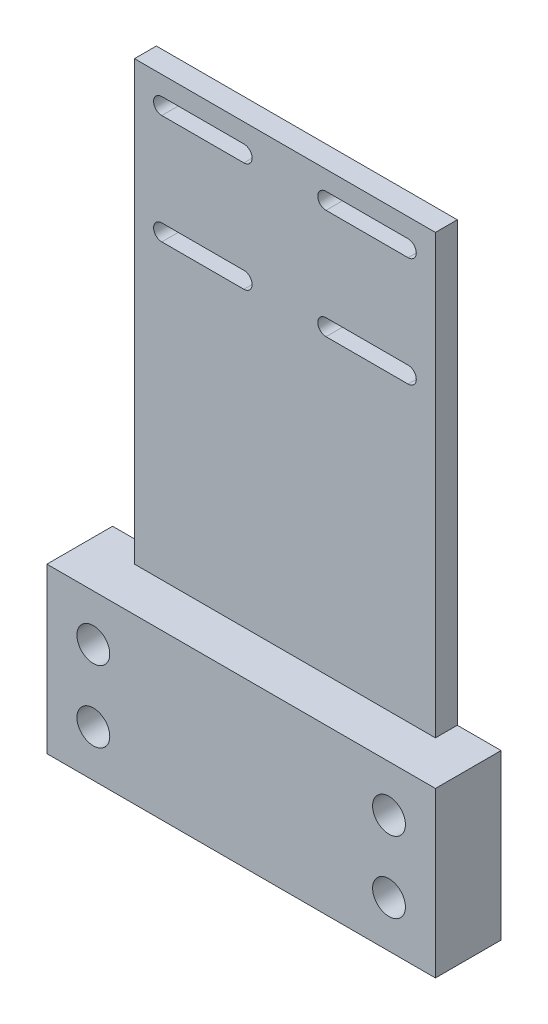
SolidWorks part; units mm, degrees
ref_plane "Front Plane" through (0, 0, 0) normal (0, 0, 1) x (1, 0, 0)
ref_plane "Top Plane" through (0, 0, 0) normal (0, 1, 0) x (1, 0, 0)
ref_plane "Right Plane" through (0, 0, 0) normal (1, 0, 0) x (0, 0, -1)
sketch "Sketch1" plane through (0, 0, 0) normal (0, 0, 1) x (1, 0, 0)
  line L0 (20, 0) -> (-20, 40) construction
  line L2 (-27.5, 35) -> (27.5, 35)
  line L3 (-27.5, 35) -> (-27.5, 5)
  line L4 (-27.5, 5) -> (27.5, 5)
  line L5 (27.5, 35) -> (27.5, 5)
  line L6 (-27.5, 35) -> (27.5, 5) construction
  line L7 (-27.5, 5) -> (27.5, 35) construction
  line L8 (22.5, 31.5) -> (7.5, 31.5)
  line L10 (22.5, 28.5) -> (7.5, 28.5)
  line L12 (22.5, 31.5) -> (7.5, 28.5) construction
  line L13 (22.5, 28.5) -> (7.5, 31.5) construction
  line L14 (22.5, 8.5) -> (7.5, 8.5)
  line L16 (22.5, 11.5) -> (7.5, 11.5)
  line L18 (22.5, 8.5) -> (7.5, 11.5) construction
  line L19 (22.5, 11.5) -> (7.5, 8.5) construction
  line L20 (-22.5, 8.5) -> (-7.5, 8.5)
  line L22 (-22.5, 11.5) -> (-7.5, 11.5)
  line L24 (-22.5, 8.5) -> (-7.5, 11.5) construction
  line L25 (-22.5, 11.5) -> (-7.5, 8.5) construction
  line L26 (-7.5, 28.5) -> (-22.5, 28.5)
  line L28 (-7.5, 31.5) -> (-22.5, 31.5)
  line L30 (-7.5, 28.5) -> (-22.5, 31.5) construction
  line L31 (-7.5, 31.5) -> (-22.5, 28.5) construction
  arc A0 (22.5, 28.5) -> (22.5, 31.5) centre (22.5, 30) ccw
  arc A1 (7.5, 28.5) -> (7.5, 31.5) centre (7.5, 30) cw
  arc A2 (22.5, 8.5) -> (22.5, 11.5) centre (22.5, 10) ccw
  arc A3 (7.5, 8.5) -> (7.5, 11.5) centre (7.5, 10) cw
  arc A4 (-7.5, 8.5) -> (-7.5, 11.5) centre (-7.5, 10) ccw
  arc A5 (-22.5, 8.5) -> (-22.5, 11.5) centre (-22.5, 10) cw
  arc A6 (-7.5, 28.5) -> (-7.5, 31.5) centre (-7.5, 30) ccw
  arc A7 (-22.5, 28.5) -> (-22.5, 31.5) centre (-22.5, 30) cw
  point P4 (0, 20)
  point P9 (15, 30)
  point P15 (15, 10)
  point P21 (-15, 10)
  point P27 (-15, 30)
  dimension "D1" = 55
  dimension "D2" = 30
  dimension "D3" = 3
  dimension "D4" = 15
  dimension "D5" = 3
  dimension "D6" = 15
extrude "Boss-Extrude1" add sketch "Sketch1" along normal blind 4
sketch "Sketch4" plane through (0, 5, 0) normal (0, -1, 0) x (1, 0, 0)
  line L1 (27.5, 4) -> (-27.5, 4)
  line L2 (27.5, 4) -> (27.5, 0)
  line L3 (27.5, 0) -> (-27.5, 0)
  line L4 (-27.5, 4) -> (-27.5, 0)
extrude "Boss-Extrude2" add sketch "Sketch4" along normal blind 80
sketch "Sketch5" plane through (-27.5, 0, 0) normal (-1, 0, 0) x (0, 0, 1)
  line L0 (0, 35) -> (0, -75) construction
  line L1 (4, -75) -> (0, -75)
  line L2 (4, -75) -> (4, -45)
  line L3 (4, -45) -> (0, -45)
  line L4 (0, -75) -> (0, -45)
  dimension "D1" = 30
extrude "Boss-Extrude3" add sketch "Sketch5" along normal blind 8
sketch "Sketch6" plane through (27.5, 0, 0) normal (1, 0, 0) x (0, 0, -1)
  line L0 (-4, -75) -> (-4, 35) construction
  line L1 (0, -75) -> (-4, -75)
  line L2 (0, -75) -> (0, -45)
  line L3 (0, -45) -> (-4, -45)
  line L4 (-4, -75) -> (-4, -45)
  dimension "D1" = 30
extrude "Boss-Extrude4" add sketch "Sketch6" along normal blind 8
sketch "Sketch7" plane through (0, 0, 4) normal (0, 0, 1) x (1, 0, 0)
  line L1 (-35.5, -75) -> (35.5, -75)
  line L2 (-35.5, -75) -> (-35.5, -45)
  line L3 (-35.5, -45) -> (35.5, -45)
  line L4 (35.5, -75) -> (35.5, -45)
extrude "Boss-Extrude5" add sketch "Sketch7" along normal blind 8
sketch "Sketch8" plane through (0, 0, 0) normal (0, 0, -1) x (-1, 0, 0)
  line L0 (-35.5, -45) -> (-27.0147, -53.4853)
  line L1 (-35.5, -75) -> (-27.0147, -66.5147)
  line L2 (35.5, -45) -> (27.0147, -53.4853)
  line L3 (35.5, -75) -> (27.0147, -66.5147)
  circle A0 centre (-27.0147, -53.4853) radius 5
  circle A1 centre (-27.0147, -66.5147) radius 5
  circle A2 centre (27.0147, -53.4853) radius 5
  circle A3 centre (27.0147, -66.5147) radius 5
sketch "Sketch9" plane through (0, 0, 12) normal (0, 0, 1) x (1, 0, 0)
  circle A0 centre (27.0147, -66.5147) radius 3
  circle A1 centre (27.0147, -53.4853) radius 3
  circle A2 centre (-27.0147, -53.4853) radius 3
  circle A3 centre (-27.0147, -66.5147) radius 3
  dimension "D1" = 6
  dimension "D2" = 6
extrude "Cut-Extrude1" cut sketch "Sketch9" against normal blind 8
extrude "Cut-Extrude4" cut sketch "Sketch8" against normal blind 4
